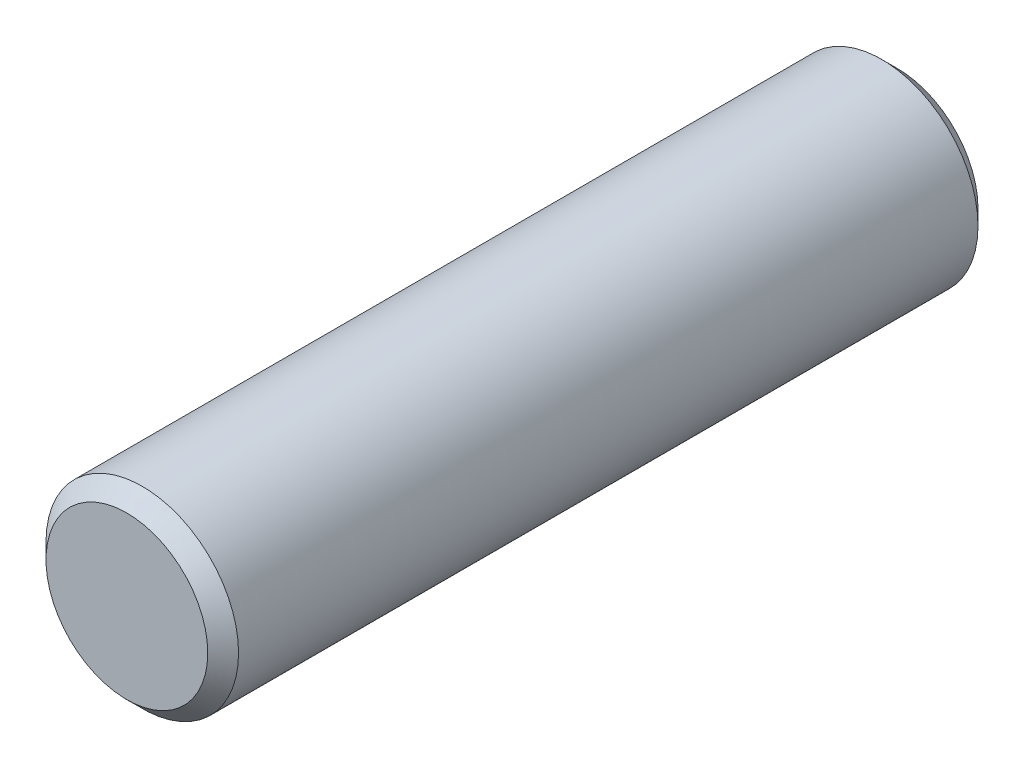
SolidWorks part; units mm, degrees
ref_plane "Front Plane" through (0, 0, 0) normal (0, 0, 1) x (1, 0, 0)
ref_plane "Top Plane" through (0, 0, 0) normal (0, 1, 0) x (1, 0, 0)
ref_plane "Right Plane" through (0, 0, 0) normal (1, 0, 0) x (0, 0, -1)
sketch "Sketch1" plane through (0, 0, 0) normal (0, 0, 1) x (1, 0, 0)
  circle A0 centre (0, 0) radius 2.5
  dimension "D1" = 5
extrude "Boss-Extrude1" add sketch "Sketch1" along normal blind 20
chamfer "Chamfer1" distance 0.4 angle 45 2 edges at (2.5, 0, 0) (2.5, 0, 20)
